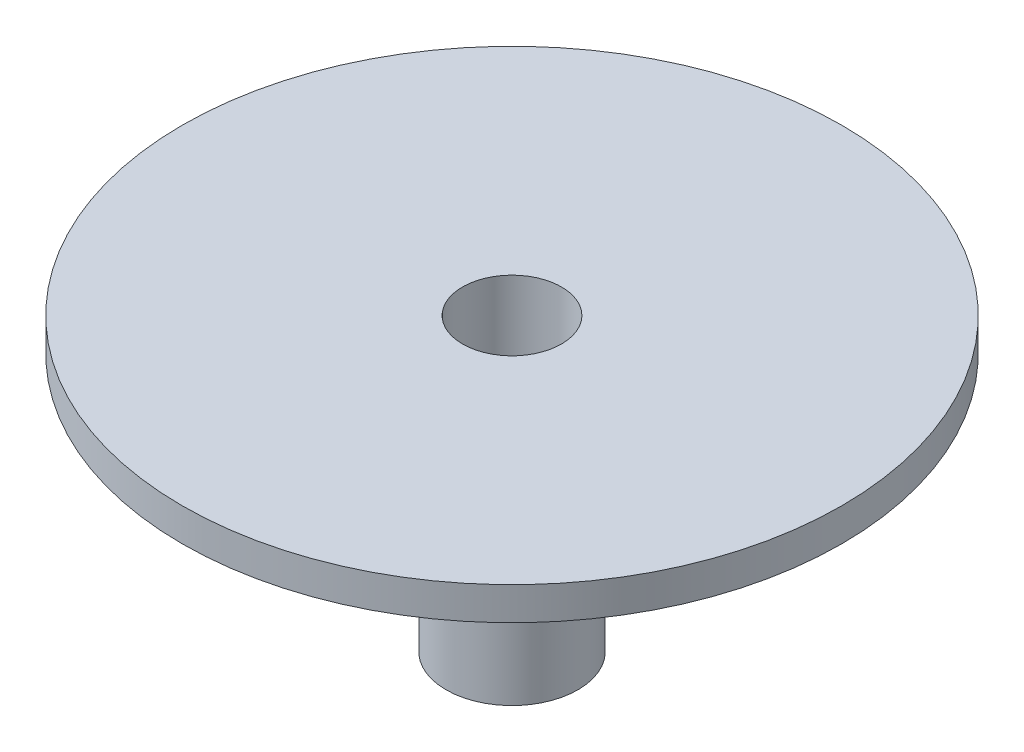
SolidWorks part; units mm, degrees
ref_plane "Front Plane" through (0, 0, 0) normal (0, 0, 1) x (1, 0, 0)
ref_plane "Top Plane" through (0, 0, 0) normal (0, 1, 0) x (1, 0, 0)
ref_plane "Right Plane" through (0, 0, 0) normal (1, 0, 0) x (0, 0, -1)
sketch "Sketch1" plane through (0, 0, 0) normal (1, 0, 0) x (0, 0, -1)
  line L0 (0, 33.1278) -> (0, -30.5795) construction
  line L1 (-42.6839, 0) -> (46.1423, 0) construction
  line L2 (-7.5, -2.75) -> (-7.5, 10.25)
  line L3 (-4.5, 13.25) -> (-4.5, -13.25)
  line L4 (-30, 10.25) -> (-30, 13.25)
  line L5 (-7.5, 10.25) -> (-30, 10.25)
  line L6 (-30, 13.25) -> (-4.5, 13.25)
  line L7 (-7.5, -2.75) -> (-6, -2.75)
  line L8 (-6, -2.75) -> (-6, -13.25)
  line L9 (-4.5, -13.25) -> (-6, -13.25)
  point P6 (-4.5, 0)
  dimension "D1" = 3
  dimension "D2" = 16
  dimension "D3" = 60
  dimension "D5" = 26.5
  dimension "D6" = 1.5
  dimension "D7" = 3
  dimension "D8" = 9
revolve "Revolve1" add sketch "Sketch1" angle 360 about L0
